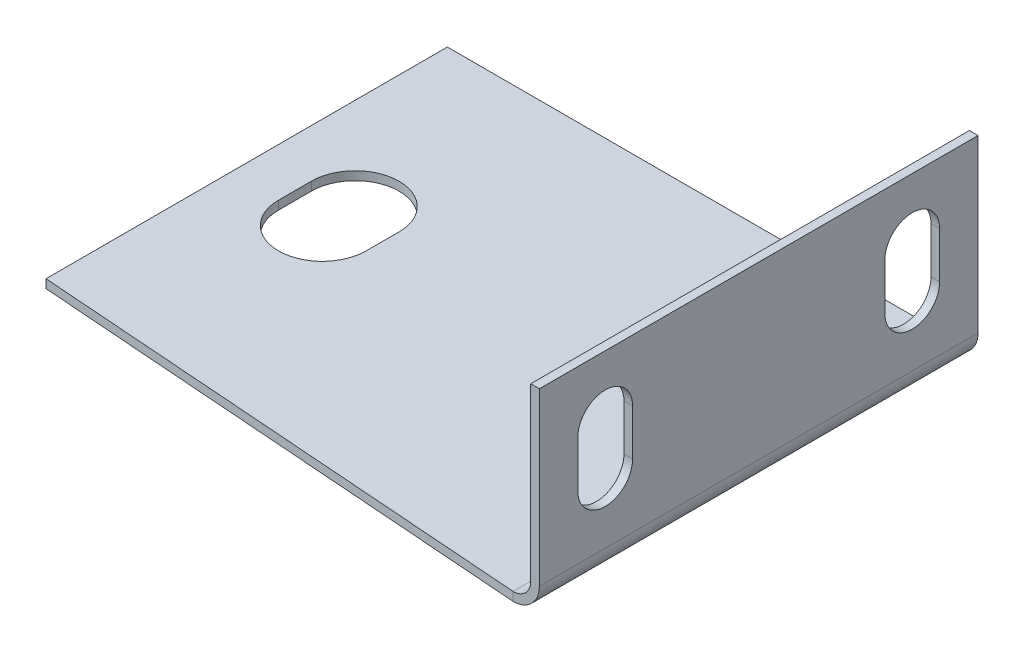
SolidWorks part; units mm, degrees
material "1023 Carbon Steel Sheet (SS)"
ref_plane "Front Plane" through (0, 0, 0) normal (0, 0, 1) x (1, 0, 0)
ref_plane "Top Plane" through (0, 0, 0) normal (0, 1, 0) x (1, 0, 0)
ref_plane "Right Plane" through (0, 0, 0) normal (1, 0, 0) x (0, 0, -1)
sketch "Sketch3" plane through (0, 0, 0) normal (0, 0, 1) x (1, 0, 0)
  line L0 (0, 0) -> (29.21, 0)
  line L1 (30.48, 1.27) -> (30.48, 11.176)
  arc A0 (30.48, 1.27) -> (29.21, 0) centre (29.21, 1.27) cw
  point P6 (30.48, 0)
  dimension "D3" = 1.27
  dimension "D1" = 30.48
  dimension "D2" = 11.176
extrude "Extrude-Thin1" add sketch "Sketch3" along normal blind 25.4 thin thin type mid plane wall 0.5
sketch "Sketch4" plane through (30.73, 0, 0) normal (1, 0, 0) x (0, 0, -1)
  line L0 (-3.81, 4.953) -> (-3.81, 7.62) construction
  line L1 (-5.3975, 4.953) -> (-5.3975, 7.62)
  line L2 (-2.2225, 4.953) -> (-2.2225, 7.62)
  line L5 (-25.4, 11.176) -> (0, 11.176) construction
  line L6 (-12.7, 11.176) -> (-12.7, 1.27) construction
  line L7 (-25.4, 1.27) -> (0, 1.27) construction
  line L8 (-21.59, 4.953) -> (-21.59, 7.62) construction
  line L9 (-20.0025, 4.953) -> (-20.0025, 7.62)
  line L10 (-23.1775, 4.953) -> (-23.1775, 7.62)
  arc A0 (-5.3975, 4.953) -> (-2.2225, 4.953) centre (-3.81, 4.953) ccw
  arc A1 (-2.2225, 7.62) -> (-5.3975, 7.62) centre (-3.81, 7.62) ccw
  arc A2 (-20.0025, 4.953) -> (-23.1775, 4.953) centre (-21.59, 4.953) cw
  arc A3 (-23.1775, 7.62) -> (-20.0025, 7.62) centre (-21.59, 7.62) cw
  point P2 (-3.81, 6.2865)
  point P18 (-21.59, 6.2865)
  dimension "D3" = 3.175
  dimension "D1" = 17.78
  dimension "D2" = 2.667
  dimension "D4" = 3.556
extrude "Cut-Extrude1" cut sketch "Sketch4" against normal through all
sketch "Sketch5" plane through (0, 0.25, 0) normal (0, 1, 0) x (1, 0, 0)
  line L0 (5.334, -12.573) -> (5.334, -10.668) construction
  line L1 (2.794, -12.573) -> (2.794, -10.668)
  line L2 (7.874, -12.573) -> (7.874, -10.668)
  line L3 (29.21, -25.4) -> (0, -25.4)
  line L4 (0, -25.4) -> (0, -23.241)
  line L5 (0, -25.4) -> (0, 0) construction
  line L6 (0, -23.241) -> (29.21, -25.4)
  line L7 (0, -23.241) -> (0, -11.6205) construction
  line L8 (0, -11.6205) -> (24.9425, -11.6205) construction
  arc A0 (2.794, -12.573) -> (7.874, -12.573) centre (5.334, -12.573) ccw
  arc A1 (7.874, -10.668) -> (2.794, -10.668) centre (5.334, -10.668) ccw
  point P2 (5.334, -11.6205)
  dimension "D5" = 1.905
  dimension "D1" = 2.159
  dimension "D2" = 11.6205
  dimension "D3" = 5.08
  dimension "D4" = 2.794
extrude "Cut-Extrude2" cut sketch "Sketch5" against normal through all
